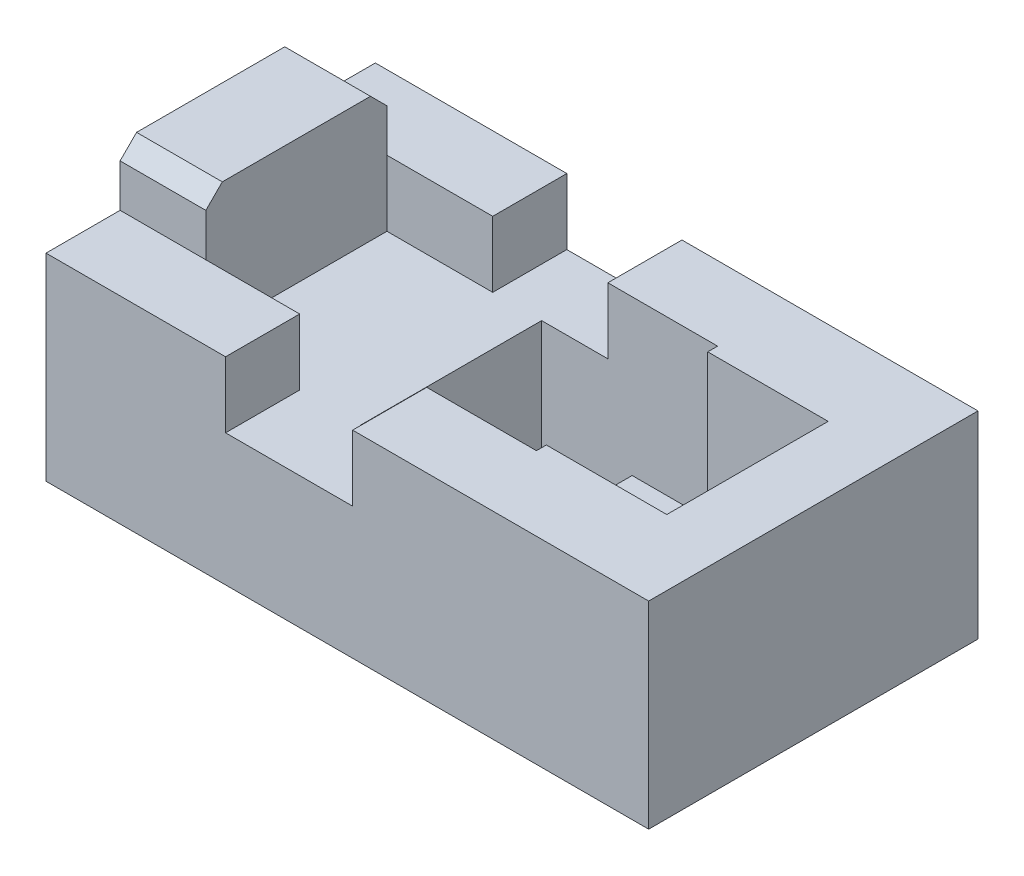
SolidWorks part; units mm, degrees
ref_plane "Front Plane" through (0, 0, 0) normal (0, 0, 1) x (1, 0, 0)
ref_plane "Top Plane" through (0, 0, 0) normal (0, 1, 0) x (1, 0, 0)
ref_plane "Right Plane" through (0, 0, 0) normal (1, 0, 0) x (0, 0, -1)
sketch "Sketch1" plane through (0, 0, 0) normal (0, 1, 0) x (1, 0, 0)
  line L1 (-9.75, -5) -> (9.75, -5)
  line L2 (-9.75, -5) -> (-9.75, 5)
  line L3 (-9.75, 5) -> (9.75, 5)
  line L4 (9.75, -5) -> (9.75, 5)
  line L5 (-9.75, -5) -> (9.75, 5) construction
  line L6 (-9.75, 5) -> (9.75, -5) construction
  point P0 (0, 0)
  dimension "D1" = 19.5
  dimension "D2" = 10
extrude "Boss-Extrude1" add sketch "Sketch1" along normal blind 4
sketch "Sketch2" plane through (0, 4, 0) normal (0, 1, 0) x (1, 0, 0)
  line L0 (9.75, -5) -> (9.75, 5) construction
  line L1 (9.75, 2.75) -> (0.75, 2.75)
  line L2 (9.75, 2.75) -> (9.75, -2.75)
  line L3 (9.75, -2.75) -> (0.75, -2.75)
  line L4 (0.75, 2.75) -> (0.75, -2.75)
  line L5 (-9.75, 5) -> (-9.75, -5) construction
  point P8 (-9.75, 0)
  point P9 (0.75, 0)
  dimension "D1" = 5.5
  dimension "D2" = 9
extrude "Cut-Extrude1" cut sketch "Sketch2" against normal blind 2.7
sketch "Sketch3" plane through (0, 4, 0) normal (0, 1, 0) x (1, 0, 0)
  line L0 (-6.55, 1.1) -> (-6.55, -1.1) construction
  line L1 (-9.75, 5) -> (-6.55, 5)
  line L2 (-9.75, 5) -> (-9.75, 1.1)
  line L3 (-9.75, 1.1) -> (-6.55, 1.1)
  line L4 (-6.55, 5) -> (-6.55, 1.1)
  line L5 (-9.75, -5) -> (-6.55, -5)
  line L6 (-9.75, -5) -> (-9.75, -1.1)
  line L7 (-9.75, -1.1) -> (-6.55, -1.1)
  line L8 (-6.55, -5) -> (-6.55, -1.1)
  line L9 (9.75, -2.75) -> (9.75, 2.75) construction
  line L10 (0.75, 2.75) -> (0.75, -2.75) construction
  point P12 (9.75, 0)
  point P13 (-6.55, 0)
  dimension "D1" = 2.2
  dimension "D2" = 7.3
extrude "Cut-Extrude2" cut sketch "Sketch3" against normal through all
sketch "Sketch4" plane through (0, 1.3, 0) normal (0, 1, 0) x (1, 0, 0)
  line L0 (0.75, -2.75) -> (9.75, -2.75) construction
  line L1 (0.75, 2.75) -> (2.4979, 2.75)
  line L2 (0.75, 2.75) -> (0.75, -2.75)
  line L3 (0.75, -2.75) -> (2.4979, -2.75)
  line L4 (2.4979, 2.75) -> (2.4979, -2.75)
extrude "Cut-Extrude3" cut sketch "Sketch4" against normal through all
chamfer "Chamfer2" distance 1 angle 45 1 edges at (2.4979, 1.3, 0)
sketch "Sketch5" plane through (9.75, 0, 0) normal (1, 0, 0) x (0, 0, -1)
  line L1 (5, 0) -> (-5, 0)
  line L2 (5, 0) -> (5, 4)
  line L3 (5, 4) -> (-5, 4)
  line L4 (-5, 0) -> (-5, 4)
extrude "Boss-Extrude2" add sketch "Sketch5" along normal blind 2
sketch "Sketch6" plane through (0, 1.3, 0) normal (0, 1, 0) x (1, 0, 0)
  line L0 (3.4979, -2.75) -> (9.75, -2.75) construction
  line L1 (9.75, 2.75) -> (8.0029, 2.75)
  line L2 (9.75, 2.75) -> (9.75, -2.75)
  line L3 (9.75, -2.75) -> (8.0029, -2.75)
  line L4 (8.0029, 2.75) -> (8.0029, -2.75)
extrude "Boss-Extrude3" add sketch "Sketch6" along normal blind 1.5
sketch "Sketch7" plane through (0, 4, 0) normal (0, 1, 0) x (1, 0, 0)
  line L0 (2.7607, 2.75) -> (2.7607, 5)
  line L1 (9.75, 2.75) -> (0.75, 2.75) construction
  line L2 (11.75, 5) -> (-6.55, 5) construction
  line L3 (2.7607, 5) -> (11.75, 5)
  line L4 (11.75, 5) -> (11.75, -5)
  line L5 (11.75, -5) -> (2.7607, -5)
  line L6 (-6.55, -5) -> (11.75, -5) construction
  line L7 (2.7607, -5) -> (2.7607, -2.75)
  line L8 (0.75, -2.75) -> (9.75, -2.75) construction
  line L9 (2.7607, -2.75) -> (9.75, -2.75)
  line L10 (9.75, -2.75) -> (9.75, 2.75)
  line L11 (9.75, 2.75) -> (2.7607, 2.75)
extrude "Boss-Extrude4" add sketch "Sketch7" along normal blind 2
sketch "Sketch9" plane through (0, 6, 0) normal (0, 1, 0) x (1, 0, 0)
  line L0 (9.75, 2.75) -> (9.75, 2.45)
  line L1 (9.75, 2.75) -> (9.75, -2.75) construction
  line L2 (9.75, 2.45) -> (6.0926, 2.45)
  line L3 (6.0926, 2.45) -> (6.0926, 2.75)
  line L4 (6.0926, 2.75) -> (9.75, 2.75)
  line L5 (9.75, -2.75) -> (6.0926, -2.75)
  line L6 (9.75, -2.75) -> (2.7607, -2.75) construction
  line L7 (6.0926, -2.75) -> (6.0926, -2.45)
  line L8 (6.0926, -2.45) -> (9.75, -2.45)
  line L9 (9.75, -2.45) -> (9.75, -2.75)
  dimension "D1" = 0.3
extrude "Boss-Extrude5" add sketch "Sketch9" against normal through all
sketch "Sketch10" plane through (0, 4, 0) normal (0, 1, 0) x (1, 0, 0)
  line L0 (2.7607, 2.75) -> (0.75, 2.75) construction
  line L1 (-6.55, 5) -> (-0.735, 5)
  line L2 (-6.55, 5) -> (-6.55, 2.75)
  line L3 (-6.55, 2.75) -> (-0.735, 2.75)
  line L4 (-0.735, 5) -> (-0.735, 2.75)
  line L5 (-6.55, -5) -> (-1.0976, -5)
  line L6 (-6.55, -5) -> (-6.55, -2.75)
  line L7 (-6.55, -2.75) -> (-1.0976, -2.75)
  line L8 (-1.0976, -5) -> (-1.0976, -2.75)
extrude "Boss-Extrude6" add sketch "Sketch10" along normal up to surface (2 mm away) up to face at (6.5344, 6, 0)
sketch "Sketch11" plane through (0, 4, 0) normal (0, 1, 0) x (1, 0, 0)
  line L0 (-1.0976, -2.75) -> (-6.55, -2.75) construction
  line L1 (-6.55, 2.75) -> (-3.9466, 2.75)
  line L2 (-6.55, 2.75) -> (-6.55, -2.75)
  line L3 (-6.55, -2.75) -> (-3.9466, -2.75)
  line L4 (-3.9466, 2.75) -> (-3.9466, -2.75)
extrude "Boss-Extrude7" add sketch "Sketch11" along normal blind 3.8
chamfer "Chamfer3" distance 0.5 angle 45 2 edges at (-5.2483, 7.8, 2.75) (-5.2483, 7.8, -2.75)
sketch "Sketch12" plane through (-6.55, 0, 0) normal (-1, 0, 0) x (0, 0, 1)
  line L1 (-5, 6) -> (5, 6)
  line L2 (-5, 6) -> (-5, 0)
  line L3 (-5, 0) -> (5, 0)
  line L4 (5, 6) -> (5, 0)
extrude "Cut-Extrude4" cut sketch "Sketch12" along normal blind 3.8
